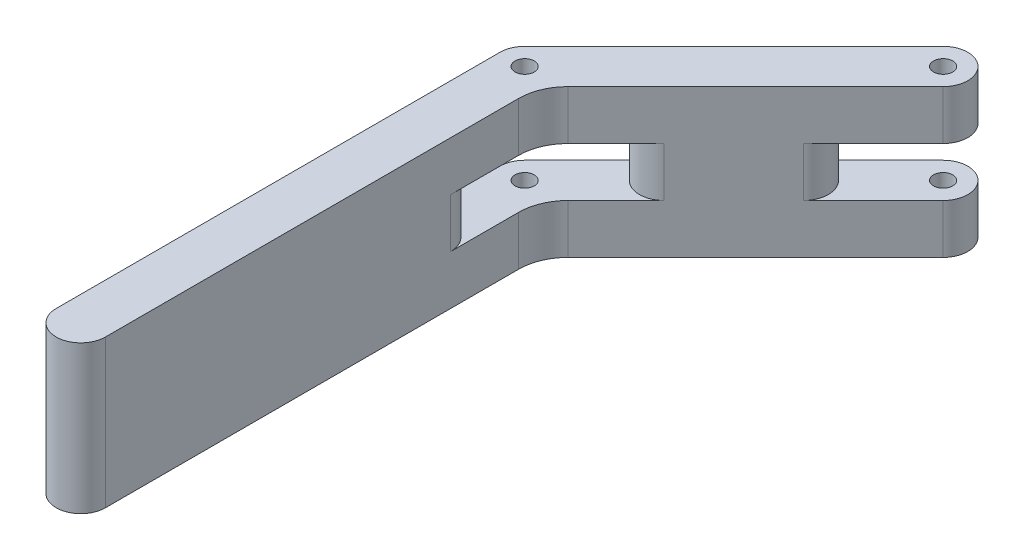
SolidWorks part; units mm, degrees
ref_plane "Plan de face" through (0, 0, 0) normal (0, 0, 1) x (1, 0, 0)
ref_plane "Plan de dessus" through (0, 0, 0) normal (0, 1, 0) x (1, 0, 0)
ref_plane "Plan de droite" through (0, 0, 0) normal (1, 0, 0) x (0, 0, -1)
sketch "Esquisse2" plane through (0, 0, 0) normal (0, 1, 0) x (1, 0, 0)
  line L0 (0, 0) -> (0, 90) construction
  line L1 (-5, 0) -> (-5, 90)
  line L2 (5, 0) -> (5, 90)
  line L3 (0, 90) -> (42.4264, 132.4264) construction
  line L4 (-3.5355, 93.5355) -> (38.8909, 135.9619)
  line L5 (3.5355, 86.4645) -> (45.9619, 128.8909)
  arc A0 (-5, 0) -> (5, 0) centre (0, 0) ccw
  arc A1 (5, 90) -> (-5, 90) centre (0, 90) ccw
  arc A2 (-3.5355, 93.5355) -> (3.5355, 86.4645) centre (0, 90) ccw
  arc A3 (45.9619, 128.8909) -> (38.8909, 135.9619) centre (42.4264, 132.4264) ccw
  circle A4 centre (42.4264, 132.4264) radius 1.95
  circle A5 centre (0, 90) radius 1.95
  point P3 (0, 45)
  point P8 (21.2132, 111.2132)
  dimension "D2" = 3.9
  dimension "D3" = 3.9
  dimension "D4" = 3.05
  dimension "D5" = 60
  dimension "D1" = 135
  dimension "D6" = 90
extrude "Boss.-Extru.1" add sketch "Esquisse2" along normal blind 10 contours A2 L1 A0 L2 L5 | L5 A3 L4 A1 L2 A4 | A1 A2 L5 L2 A5
fillet "Congé1" radius 10 1 edges at (5, 5, -87.9289)
sketch "Esquisse3" plane through (0, 10, 0) normal (0, 1, 0) x (1, 0, 0)
  line L0 (0, 0) -> (0, 70) construction
  line L1 (-5, 0) -> (-5, 70)
  line L2 (5, 0) -> (5, 70)
  line L3 (28.2843, 118.2843) -> (14.1421, 104.1421) construction
  line L4 (31.8198, 114.7487) -> (17.6777, 100.6066)
  line L5 (24.7487, 121.8198) -> (10.6066, 107.6777)
  line L6 (5, 0) -> (5, 83.7868) construction
  line L7 (-3.5355, 93.5355) -> (38.8909, 135.9619) construction
  line L9 (7.9289, 90.8579) -> (45.9619, 128.8909) construction
  arc A0 (-5, 0) -> (5, 0) centre (0, 0) ccw
  arc A1 (5, 70) -> (-5, 70) centre (0, 70) ccw
  arc A2 (31.8198, 114.7487) -> (24.7487, 121.8198) centre (28.2843, 118.2843) ccw
  arc A3 (10.6066, 107.6777) -> (17.6777, 100.6066) centre (14.1421, 104.1421) ccw
  circle A4 centre (0, 90) radius 1.95 construction
  point P3 (0, 35)
  point P8 (21.2132, 111.2132)
  dimension "D1" = 20
  dimension "D2" = 20
  dimension "D3" = 70
extrude "Boss.-Extru.2" add sketch "Esquisse3" along normal blind 10
sketch "Esquisse4" plane through (0, 20, 0) normal (0, 1, 0) x (1, 0, 0)
  line L0 (5, 0) -> (5, 70) construction
  line L1 (-5, 70) -> (-5, 0) construction
  line L2 (7.9289, 90.8579) -> (17.6777, 100.6066) construction
  line L3 (10.6066, 107.6777) -> (-3.5355, 93.5355) construction
  line L4 (-5, 90) -> (-5, 70) construction
  line L5 (5, 70) -> (5, 83.7868) construction
  line L6 (24.7487, 121.8198) -> (10.6066, 107.6777) construction
  line L7 (17.6777, 100.6066) -> (31.8198, 114.7487) construction
  line L8 (38.8909, 135.9619) -> (24.7487, 121.8198) construction
  line L9 (31.8198, 114.7487) -> (45.9619, 128.8909) construction
  line L10 (5, 0) -> (5, 70)
  line L11 (-5, 70) -> (-5, 0)
  line L12 (7.9289, 90.8579) -> (17.6777, 100.6066)
  line L13 (10.6066, 107.6777) -> (-3.5355, 93.5355)
  line L14 (-5, 90) -> (-5, 70)
  line L15 (5, 70) -> (5, 83.7868)
  line L16 (24.7487, 121.8198) -> (10.6066, 107.6777)
  line L17 (17.6777, 100.6066) -> (31.8198, 114.7487)
  line L18 (38.8909, 135.9619) -> (24.7487, 121.8198)
  line L19 (31.8198, 114.7487) -> (45.9619, 128.8909)
  arc A0 (-5, 0) -> (5, 0) centre (0, 0) ccw construction
  arc A1 (5, 70) -> (-5, 70) centre (0, 70) ccw construction
  arc A2 (10.6066, 107.6777) -> (17.6777, 100.6066) centre (14.1421, 104.1421) ccw construction
  arc A3 (-3.5355, 93.5355) -> (-5, 90) centre (0, 90) ccw construction
  arc A4 (5, 70) -> (-5, 70) centre (0, 70) ccw construction
  arc A5 (7.9289, 90.8579) -> (5, 83.7868) centre (15, 83.7868) ccw construction
  arc A6 (31.8198, 114.7487) -> (24.7487, 121.8198) centre (28.2843, 118.2843) ccw construction
  arc A7 (10.6066, 107.6777) -> (17.6777, 100.6066) centre (14.1421, 104.1421) ccw construction
  arc A8 (31.8198, 114.7487) -> (24.7487, 121.8198) centre (28.2843, 118.2843) ccw construction
  arc A9 (45.9619, 128.8909) -> (38.8909, 135.9619) centre (42.4264, 132.4264) ccw construction
  arc A10 (-5, 0) -> (5, 0) centre (0, 0) ccw
  arc A11 (5, 70) -> (-5, 70) centre (0, 70) ccw
  arc A12 (10.6066, 107.6777) -> (17.6777, 100.6066) centre (14.1421, 104.1421) ccw
  arc A13 (-3.5355, 93.5355) -> (-5, 90) centre (0, 90) ccw
  arc A14 (5, 70) -> (-5, 70) centre (0, 70) ccw
  arc A15 (7.9289, 90.8579) -> (5, 83.7868) centre (15, 83.7868) ccw
  arc A16 (31.8198, 114.7487) -> (24.7487, 121.8198) centre (28.2843, 118.2843) ccw
  arc A17 (10.6066, 107.6777) -> (17.6777, 100.6066) centre (14.1421, 104.1421) ccw
  arc A18 (31.8198, 114.7487) -> (24.7487, 121.8198) centre (28.2843, 118.2843) ccw
  arc A19 (45.9619, 128.8909) -> (38.8909, 135.9619) centre (42.4264, 132.4264) ccw
  circle A20 centre (0, 90) radius 1.95 construction
  circle A21 centre (42.4264, 132.4264) radius 1.95 construction
  circle A22 centre (0, 90) radius 1.95
  circle A23 centre (42.4264, 132.4264) radius 1.95
  arc M1 (-5, 0) -> (5, 0) centre (0, 0) ccw
  line M2 (5, 0) -> (5, 70)
  arc M3 (5, 70) -> (-5, 70) centre (0, 70) ccw
  line M4 (-5, 70) -> (-5, 0)
extrude "Boss.-Extru.3" add sketch "Esquisse4" along normal blind 10 contours L19 A19 L18 A16 A23 | L17 A16 L16 A12 | A15 L12 A12 L13 A13 L14 L15 A22 M3 | M4 M1 M2 M3
